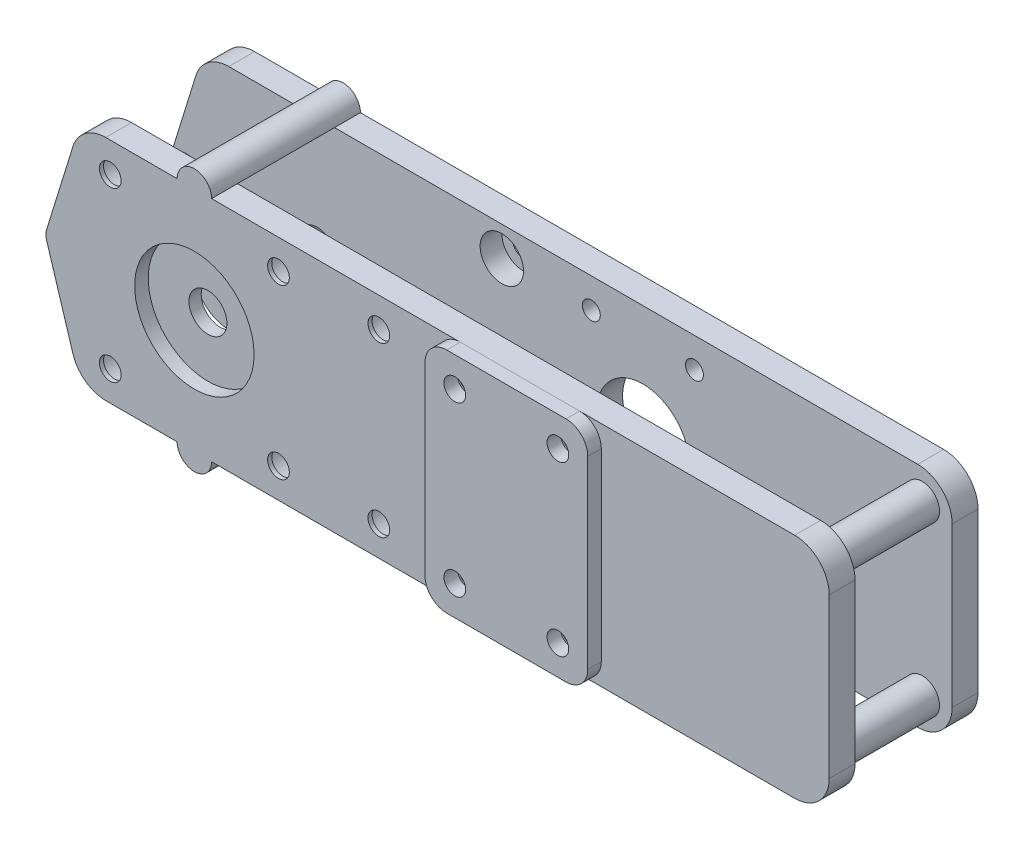
SolidWorks part; units mm, degrees
ref_plane "Front Plane" through (0, 0, 0) normal (0, 0, 1) x (1, 0, 0)
ref_plane "Top Plane" through (0, 0, 0) normal (0, 1, 0) x (1, 0, 0)
ref_plane "Right Plane" through (0, 0, 0) normal (1, 0, 0) x (0, 0, -1)
sketch "Sketch1" plane through (0, 0, 0) normal (0, 0, 1) x (1, 0, 0)
  line L0 (0, 0) -> (60, 0) construction
  line L3 (-15.5, 21) -> (-15.5, 15.5) construction
  line L8 (-21, 21) -> (21, 21)
  line L9 (-21, 21) -> (-21, -21)
  line L10 (-21, -21) -> (21, -21)
  line L11 (21, 21) -> (21, -21)
  line L12 (-21, 21) -> (21, -21) construction
  line L13 (-21, -21) -> (21, 21) construction
  line L14 (-15.5, 15.5) -> (-21, 15.5) construction
  line L15 (34, 15.5) -> (34, -15.5) construction
  line L16 (21, 21) -> (47, 21)
  line L17 (21, 21) -> (21, -149.1981)
  line L18 (21, -149.1981) -> (47, -149.1981)
  line L19 (47, 21) -> (47, -149.1981)
  circle A0 centre (0, 0) radius 17 construction
  circle A1 centre (60, 0) radius 47 construction
  circle A2 centre (0, 0) radius 15
  circle A3 centre (60, 0) radius 45
  circle A6 centre (-15.5, 15.5) radius 2
  circle A7 centre (15.5, 15.5) radius 2
  circle A8 centre (-15.5, -15.5) radius 2
  circle A9 centre (15.5, -15.5) radius 2
  circle A10 centre (34, 15.5) radius 2
  circle A11 centre (34, -15.5) radius 2
  circle A12 centre (0, 0) radius 8.5
  circle A14 centre (60, 0) radius 8.5
  point P33 (34, 21)
  dimension "D1" = 34
  dimension "D2" = 94
  dimension "D3" = 30
  dimension "D4" = 90
  dimension "D5" = 17
  dimension "D9" = 4
  dimension "D13" = 4
  dimension "D7" = 42
  dimension "D8" = 31
  dimension "D10" = 26
sketch "Sketch2" plane through (0, 0, 0) normal (0, 0, 1) x (1, 0, 0)
  line L0 (-21, -21) -> (21, -21) construction
  line L1 (-21, 21) -> (117, 21)
  line L2 (-21, 21) -> (-21, -21)
  line L3 (-21, -21) -> (117, -21)
  line L4 (117, 21) -> (117, -21)
  circle A1 centre (15.5, -15.5) radius 2 construction
  circle A3 centre (15.5, 15.5) radius 2 construction
  circle A12 centre (111.5, 15.5) radius 2
  circle A13 centre (111.5, -15.5) radius 2
  circle A14 centre (60, 0) radius 47 construction
  circle A15 centre (111.5, -15.5) radius 3.175 construction
  circle A17 centre (34, -15.5) radius 2 construction
  circle A18 centre (34, 15.5) radius 2 construction
  circle A19 centre (34, -15.5) radius 2
  circle A20 centre (34, 15.5) radius 2
  circle A22 centre (0, 0) radius 3.5
  circle A23 centre (60, 0) radius 8.5 construction
  circle A24 centre (60, 0) radius 8.5
  point P10 (0, 0)
  dimension "D1" = 10
  dimension "D2" = 5.5
  dimension "D3" = 6.35
  dimension "D4" = 7
extrude "Boss-Extrude1" add sketch "Sketch2" along normal mid plane 4.7625
sketch "Sketch3" plane through (0, 0, -2.3813) normal (0, 0, -1) x (-1, 0, 0)
  circle A0 centre (-34, 15.5) radius 2
  circle A1 centre (-34, -15.5) radius 4
  circle A2 centre (-34, 15.5) radius 4
  circle A3 centre (-15.5, 15.5) radius 4
  circle A4 centre (15.5, 15.5) radius 4
  circle A5 centre (-15.5, -15.5) radius 4
  circle A6 centre (15.5, -15.5) radius 4
  dimension "D1" = 4
  dimension "D2" = 8
extrude "Cut-Extrude1" cut sketch "Sketch3" against normal blind 4
sketch "Sketch4" plane through (0, 0, -2.3813) normal (0, 0, -1) x (-1, 0, 0)
  circle A0 centre (-111.5, -15.5) radius 3.175 construction
  circle A1 centre (-111.5, -15.5) radius 3.175
  circle A2 centre (-111.5, 15.5) radius 3.175
  circle A5 centre (-111.5, 15.5) radius 2
  circle A6 centre (-111.5, -15.5) radius 2
ref_plane "Plane1" through (0, 0, -11.3312) normal (0, 0, -1) x (-1, 0, 0)
extrude "Boss-Extrude2" add sketch "Sketch4" along normal blind 17.9
sketch "Sketch5" plane through (0, 0, -2.3813) normal (0, 0, -1) x (-1, 0, 0)
  line L0 (21, 21) -> (21, -21) construction
  line L1 (21, -21) -> (27.2081, -0.9386)
  line L2 (21, 21) -> (27.2081, 0.9386)
  line L3 (21, 21) -> (21, -21)
  arc A0 (27.2081, -0.9386) -> (27.2081, 0.9386) centre (24.175, 0) ccw
  point P5 (24.175, 0.7154)
  point P7 (21, 0)
  dimension "D1" = 6.35
sketch "Sketch6" plane through (0, 0, -2.3813) normal (0, 0, -1) x (-1, 0, 0)
  circle A0 centre (-15.5, 15.5) radius 2 construction
  circle A1 centre (15.5, 15.5) radius 2 construction
  circle A2 centre (15.5, -15.5) radius 2 construction
  circle A3 centre (-15.5, -15.5) radius 2 construction
  circle A16 centre (-15.5, 15.5) radius 2
  circle A17 centre (15.5, 15.5) radius 2
  circle A18 centre (15.5, -15.5) radius 2
  circle A19 centre (-15.5, -15.5) radius 2
extrude "Cut-Extrude2" cut sketch "Sketch6" against normal blind 10
extrude "Boss-Extrude3" add sketch "Sketch5" against normal up to surface (4.7625 mm away) up to face at (17.5, -15.5, 2.3812)
mirror "Mirror2" about plane through (0, 0, -11.3312) normal (0, 0, -1) of "Boss-Extrude3", "Boss-Extrude1"
sketch "Sketch7" plane through (0, 0, -20.2812) normal (0, 0, 1) x (1, 0, 0)
  circle A5 centre (-24.175, 0) radius 3.175
  arc A6 (-27.2081, 0.9386) -> (-27.2081, -0.9386) centre (-24.175, 0) ccw construction
  dimension "D1" = 6.35
extrude "Boss-Extrude4" add sketch "Sketch7" along normal up to surface (17.9 mm away) contours A5 up to face at (114.675, 15.5, -2.3813)
fillet "Fillet1" radius 6.35 8 edges at (-21, 21, -22.6625) (-21, -21, -22.6625) (117, -21, -22.6625) (117, 21, -22.6625) (117, -21, 0) (-21, -21, 0) (-21, 21, 0) (117, 21, 0)
sketch "Sketch8" plane through (0, 0, -25.0437) normal (0, 0, -1) x (-1, 0, 0)
  line L0 (16.3179, -21) -> (-110.65, -21) construction
  line L1 (-3.175, -21) -> (3.175, -21)
  line L2 (0, 0) -> (27.35, 0) construction
  arc A0 (-3.175, -21) -> (3.175, -21) centre (0, -21) ccw
  arc A1 (27.2081, -0.9386) -> (27.2081, 0.9386) centre (24.175, 0) ccw construction
  arc A2 (-3.175, 21) -> (3.175, 21) centre (0, 21) cw
  line M9 (16.3179, 21) -> (-110.65, 21)
  line M13 (-110.65, -21) -> (16.3179, -21)
  dimension "D1" = 6.35
extrude "Boss-Extrude5" add sketch "Sketch8" against normal up to surface (27.425 mm away) contours A2 M9 | A0 M13 up to face at (17.5, -15.5, 2.3812)
sketch "Sketch9" plane through (0, 0, -20.2812) normal (0, 0, 1) x (1, 0, 0)
  circle A0 centre (34, -15.5) radius 4 construction
  circle A1 centre (34, 15.5) radius 4 construction
  circle A2 centre (34, -15.5) radius 4
  circle A3 centre (34, 15.5) radius 4
extrude "Cut-Extrude4" cut sketch "Sketch9" against normal blind 4
sketch "Sketch10" plane through (0, 0, 2.3813) normal (0, 0, 1) x (1, 0, 0)
  circle A0 centre (0, 0) radius 11.0046
  dimension "D1" = 22.0091
extrude "Cut-Extrude5" cut sketch "Sketch10" against normal blind 2.5
sketch "Sketch11" plane through (0, 0, 2.3813) normal (0, 0, 1) x (1, 0, 0)
  line L0 (3.175, 21) -> (110.65, 21) construction
  line L1 (45, 21) -> (75, 21) construction
  line L2 (45, 21) -> (45, -21) construction
  line L3 (45, -21) -> (75, -21) construction
  line L4 (75, 21) -> (75, -21) construction
  line L5 (3.175, -21) -> (110.65, -21) construction
  line L6 (60, 0) -> (60, 21) construction
  line L7 (45, 15.5) -> (50.5, 15.5) construction
  line L8 (50.5, 15.5) -> (50.5, 21) construction
  line L9 (60, 0) -> (75, 0) construction
  circle A0 centre (50.5, 15.5) radius 1.65
  circle A2 centre (34, 15.5) radius 2 construction
  circle A3 centre (34, 15.5) radius 2 construction
  circle A4 centre (69.5, 15.5) radius 1.65
  circle A5 centre (69.5, -15.5) radius 1.65
  circle A6 centre (50.5, -15.5) radius 1.65
  dimension "D2" = 3.3
  dimension "D1" = 30
extrude "Cut-Extrude6" cut sketch "Sketch11" against normal through all both and the other way through all
sketch "Sketch12" plane through (0, 0, 2.3813) normal (0, 0, 1) x (1, 0, 0)
  line L0 (60, 0) -> (60, 21) construction
  line L1 (49, 21) -> (71, 21)
  line L2 (45, 17) -> (45, -17)
  line L3 (49, -21) -> (71, -21)
  line L4 (75, 17) -> (75, -17)
  line L5 (60, 0) -> (60, 21) construction
  line L6 (60, 0) -> (75, 0) construction
  line L7 (60, 0) -> (75, 0) construction
  circle A1 centre (50.5, 15.5) radius 2
  circle A2 centre (69.5, 15.5) radius 2
  circle A4 centre (69.5, -15.5) radius 2
  circle A5 centre (50.5, -15.5) radius 2
  arc A6 (75, -17) -> (71, -21) centre (71, -17) cw
  arc A7 (49, -21) -> (45, -17) centre (49, -17) cw
  arc A8 (75, 17) -> (71, 21) centre (71, 17) ccw
  arc A9 (49, 21) -> (45, 17) centre (49, 17) ccw
  point P20 (75, -21)
  point P27 (45, 21)
  dimension "D1" = 4
  dimension "D2" = 4
extrude "Boss-Extrude6" add sketch "Sketch12" along normal blind 2.5 separate body
